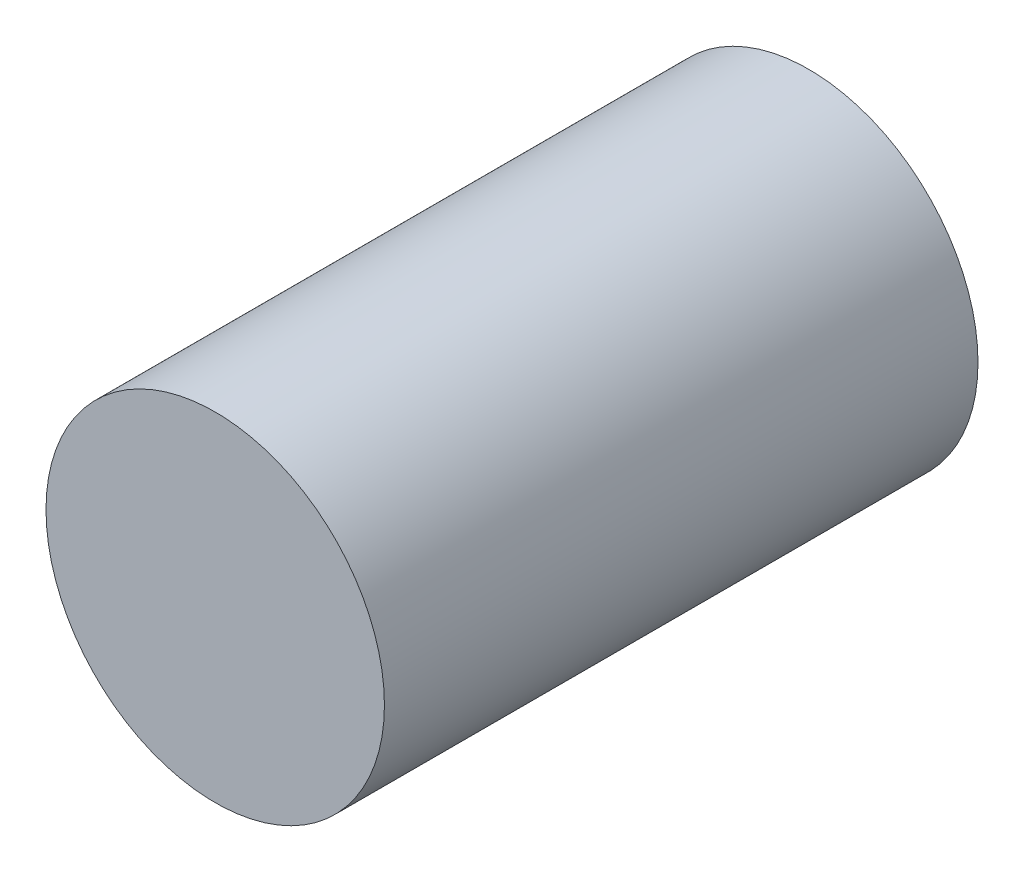
SolidWorks part; units mm, degrees
ref_plane "Front Plane" through (0, 0, 0) normal (0, 0, 1) x (1, 0, 0)
ref_plane "Top Plane" through (0, 0, 0) normal (0, 1, 0) x (1, 0, 0)
ref_plane "Right Plane" through (0, 0, 0) normal (1, 0, 0) x (0, 0, -1)
sketch "Sketch1" plane through (0, 0, 0) normal (0, 0, 1) x (1, 0, 0)
  circle A0 centre (0, 0) radius 3.25
  dimension "D1" = 6.5
extrude "Extrude1" add sketch "Sketch1" along normal blind 11.4
